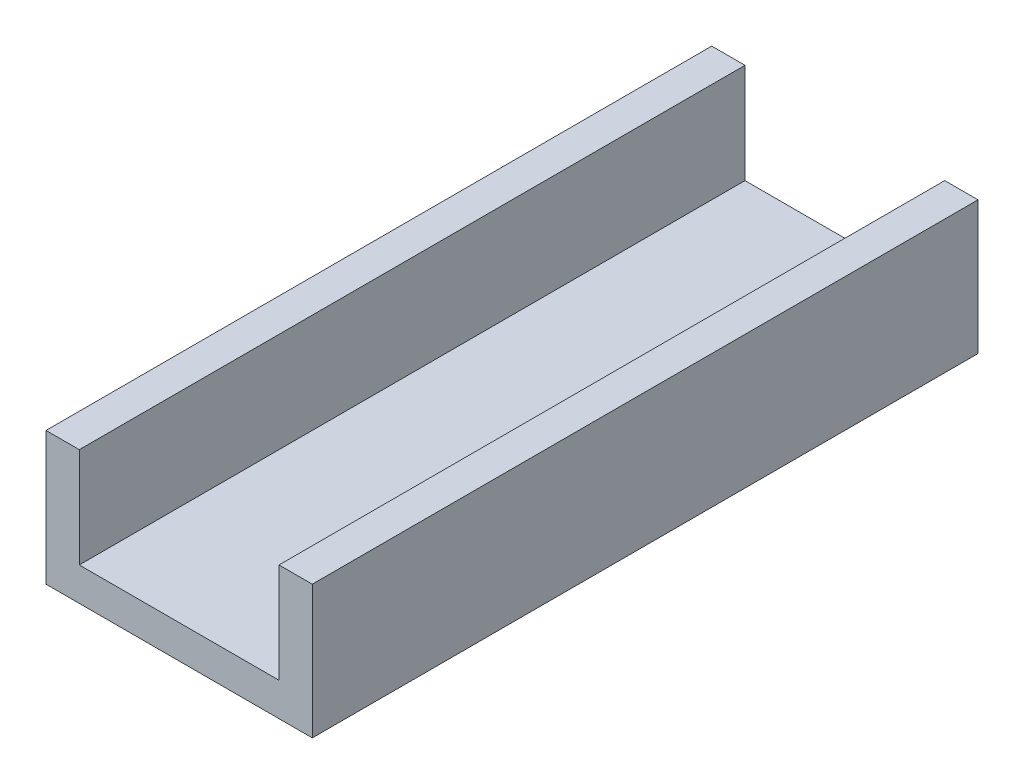
SolidWorks part; units mm, degrees
ref_plane "Front Plane" through (0, 0, 0) normal (0, 0, 1) x (1, 0, 0)
ref_plane "Top Plane" through (0, 0, 0) normal (0, 1, 0) x (1, 0, 0)
ref_plane "Right Plane" through (0, 0, 0) normal (1, 0, 0) x (0, 0, -1)
sketch "Sketch1" plane through (0, 0, 0) normal (0, 0, 1) x (1, 0, 0)
  line L0 (0, 30) -> (0, 0)
  line L1 (0, 0) -> (60, 0)
  line L2 (60, 0) -> (60, 30)
  dimension "D1" = 60
  dimension "D2" = 30
extrude "Extrude-Thin1" add sketch "Sketch1" along normal blind 200 thin
